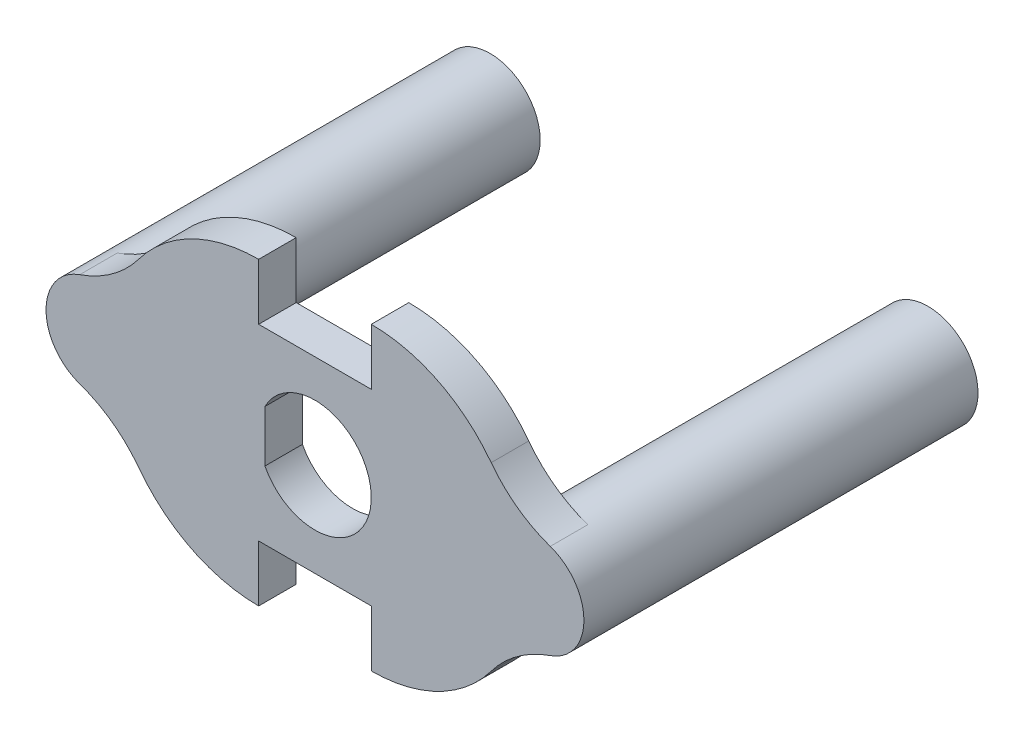
SolidWorks part; units mm, degrees
ref_plane "前视基准面" through (0, 0, 0) normal (0, 0, 1) x (1, 0, 0)
ref_plane "上视基准面" through (0, 0, 0) normal (0, 1, 0) x (1, 0, 0)
ref_plane "右视基准面" through (0, 0, 0) normal (1, 0, 0) x (0, 0, -1)
sketch "草图1" plane through (0, 0, 0) normal (0, 0, 1) x (1, 0, 0)
  line L0 (0, 0) -> (23.5174, 0) construction
  line L1 (0, 0) -> (0, 15) construction
  line L2 (-4.5, 7.5) -> (4.5, 7.5)
  line L3 (4.5, 7.5) -> (4.5, 12)
  line L4 (-4.5, 7.5) -> (-4.5, 12)
  line L5 (4.5, -7.5) -> (4.5, -12)
  line L6 (-4.5, -7.5) -> (4.5, -7.5)
  line L7 (-4.5, -7.5) -> (-4.5, -12)
  arc A0 (4.5, 12) -> (14.0874, 7.2168) centre (4.5, 0) cw
  arc A1 (18.8077, -3.7802) -> (18.8077, 3.7802) centre (17.5, 0) ccw
  arc A2 (14.0874, 7.2168) -> (18.8077, 3.7802) centre (22.0769, 13.2307) ccw
  arc A3 (-14.0874, 7.2168) -> (-18.8077, 3.7802) centre (-22.0769, 13.2307) cw
  arc A4 (-4.5, 12) -> (-14.0874, 7.2168) centre (-4.5, 0) ccw
  arc A5 (14.0874, -7.2168) -> (18.8077, -3.7802) centre (22.0769, -13.2307) cw
  arc A6 (4.5, -12) -> (14.0874, -7.2168) centre (4.5, 0) ccw
  arc A7 (-4.5, -12) -> (-14.0874, -7.2168) centre (-4.5, 0) cw
  arc A8 (-14.0874, -7.2168) -> (-18.8077, -3.7802) centre (-22.0769, -13.2307) ccw
  arc A9 (-18.8077, -3.7802) -> (-18.8077, 3.7802) centre (-17.5, 0) cw
  point P13 (0, 0)
  point P14 (18.4076, 4.8527)
  point P15 (0, 0)
  point P22 (0, 7.5)
  dimension "D1" = 7.5
  dimension "D2" = 8
  dimension "D6" = 12
  dimension "D7" = 10
  dimension "D3" = 4.5
  dimension "D4" = 17.5
  dimension "D5" = 4.5
extrude "凸台-拉伸1" add sketch "草图1" against normal mid plane 3
sketch "草图4" plane through (0, 0, 1.5) normal (0, 0, 1) x (1, 0, 0)
  line L0 (-4, 2.0616) -> (-4, -2.0616)
  arc A0 (-4, -2.0616) -> (-4, 2.0616) centre (0, 0) ccw
  dimension "D1" = 9
  dimension "4" = 4
extrude "切除-拉伸1" cut sketch "草图4" against normal through all
sketch "草图5" plane through (0, 0, -1.5) normal (0, 0, -1) x (-1, 0, 0)
  circle A0 centre (-17.5, 0) radius 4
  arc A1 (-18.8077, 3.7802) -> (-18.8077, -3.7802) centre (-17.5, 0) ccw construction
extrude "凸台-拉伸2" add sketch "草图5" along normal blind 28.5
sketch "草图8" plane through (0, 0, -30) normal (0, 0, -1) x (-1, 0, 0)
  circle A0 centre (-17.5, 0) radius 1.5
  dimension "D1" = 3
extrude "切除-拉伸2" cut sketch "草图8" against normal blind 10.5
mirror "镜向2" about plane through (0, 0, 0) normal (1, 0, 0) of "切除-拉伸2", "凸台-拉伸2"
ref_plane "基准面8" through (0, 0, -15.5) normal (0, 0, -1) x (-1, 0, 0)
sketch "草图10" plane through (0, 0, -15.5) normal (0, 0, -1) x (-1, 0, 0)
  line L0 (20.1458, -3) -> (20.1458, 3)
  circle A0 centre (17.5, 0) radius 4 construction
  arc A1 (20.1458, -3) -> (20.1458, 3) centre (17.5, 0) ccw
  dimension "D1" = 6
extrude "切除-拉伸3" cut sketch "草图10" against normal mid plane 6
sketch "草图11" plane through (-20.1458, 0, 0) normal (-1, 0, 0) x (0, 0, 1)
  line L2 (-18.5, 0) -> (-12.5, 0) construction
  line L3 (-18.5, -3) -> (-18.5, 3) construction
  line L4 (-12.5, 3) -> (-12.5, -3) construction
  line L5 (-15.5, 3) -> (-15.5, -3) construction
  line L6 (-12.5, 3) -> (-18.5, 3) construction
  line L7 (-12.5, -3) -> (-18.5, -3) construction
  circle A0 centre (-15.5, 0) radius 1.5
  point P4 (-16.7845, 0)
  point P15 (0, 0)
  dimension "D1" = 3
extrude "切除-拉伸4" cut sketch "草图11" against normal blind 5
